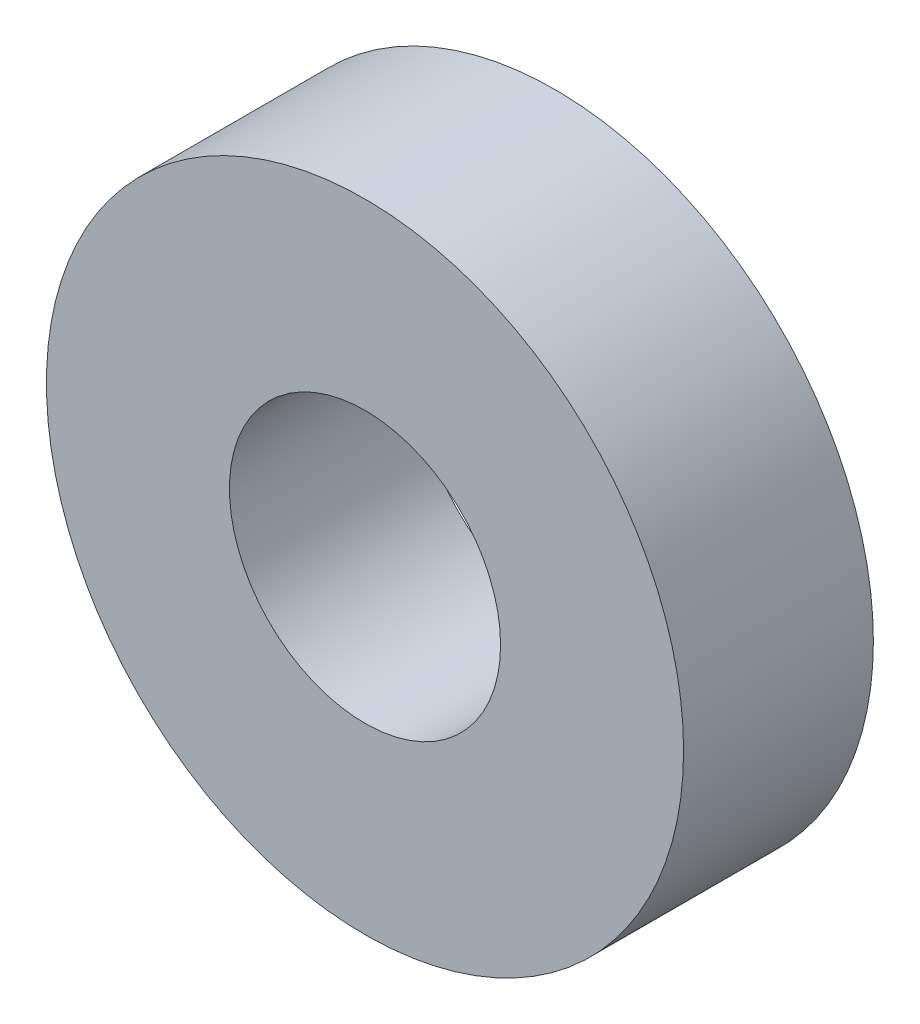
SolidWorks part; units mm, degrees
ref_plane "Спереди" through (0, 0, 0) normal (0, 0, 1) x (1, 0, 0)
ref_plane "Сверху" through (0, 0, 0) normal (0, 1, 0) x (1, 0, 0)
ref_plane "Справа" through (0, 0, 0) normal (1, 0, 0) x (0, 0, -1)
sketch "Эскиз1" plane through (0, 0, 0) normal (0, 0, 1) x (1, 0, 0)
  circle A0 centre (0, 0) radius 23.5
  circle A1 centre (0, 0) radius 10
extrude "Purchased_bearing_envelope" add sketch "Эскиз1" along normal blind 14 from offset 40
